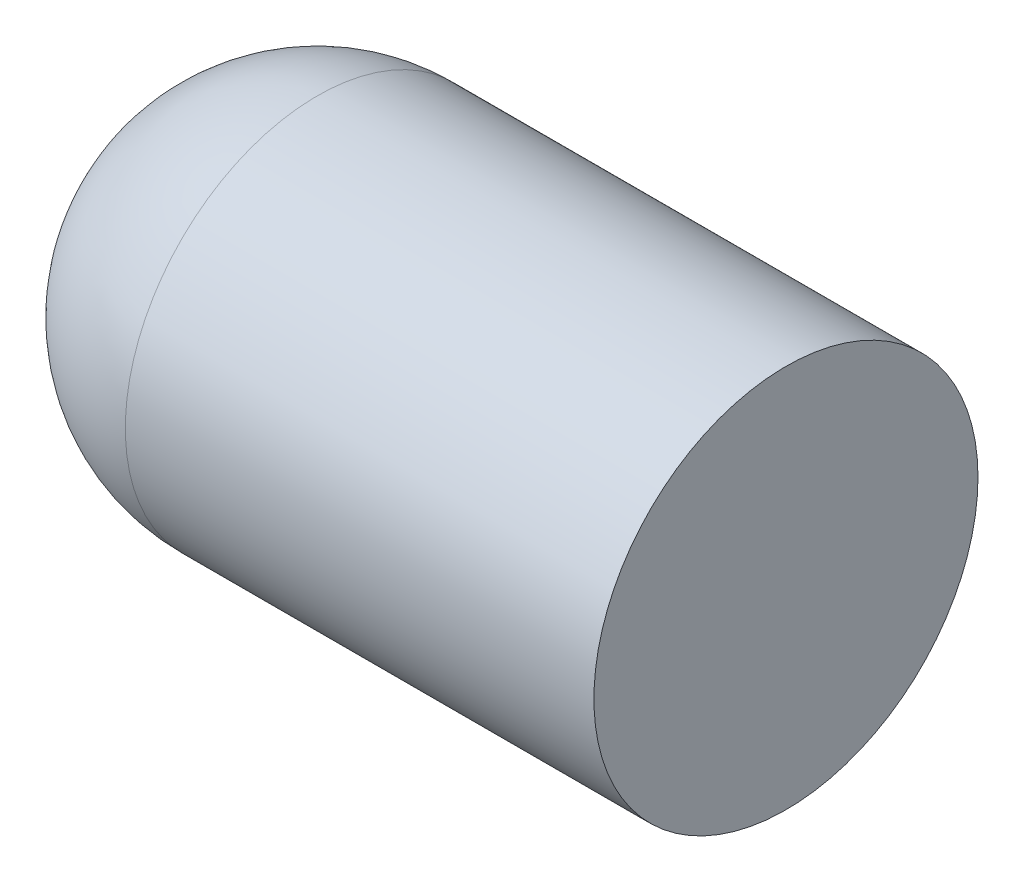
SolidWorks part; units mm, degrees
ref_plane "Front Plane" through (0, 0, 0) normal (0, 0, 1) x (1, 0, 0)
ref_plane "Top Plane" through (0, 0, 0) normal (0, 1, 0) x (1, 0, 0)
ref_plane "Right Plane" through (0, 0, 0) normal (1, 0, 0) x (0, 0, -1)
sketch "Sketch1" plane through (0, 0, 0) normal (1, 0, 0) x (0, 0, -1)
  line L0 (0, -2.5) -> (0, 2.5)
  arc A0 (0, 2.5) -> (0, -2.5) centre (0, 0) cw
  point P5 (0, 0)
  dimension "D1" = 5
revolve "Revolve1" add sketch "Sketch1" angle 180 about L0
sketch "Sketch2" plane through (0, 0, 0) normal (1, 0, 0) x (0, 0, -1)
  circle A0 centre (0, 0) radius 2.5
extrude "Boss-Extrude1" add sketch "Sketch2" along normal blind 6.1
sketch "Sketch3" plane through (0, 0, 0) normal (0, 0, 1) x (1, 0, 0)
  line L0 (0, 0) -> (-10, 1.7633)
  line L1 (0, 0) -> (-10, 0)
  line L2 (-10, 1.7633) -> (-10, 0)
  dimension "D1" = 10
  dimension "D2" = 10
revolve "Revolve2" [suppressed] add sketch "Sketch3" angle 360 about L1
